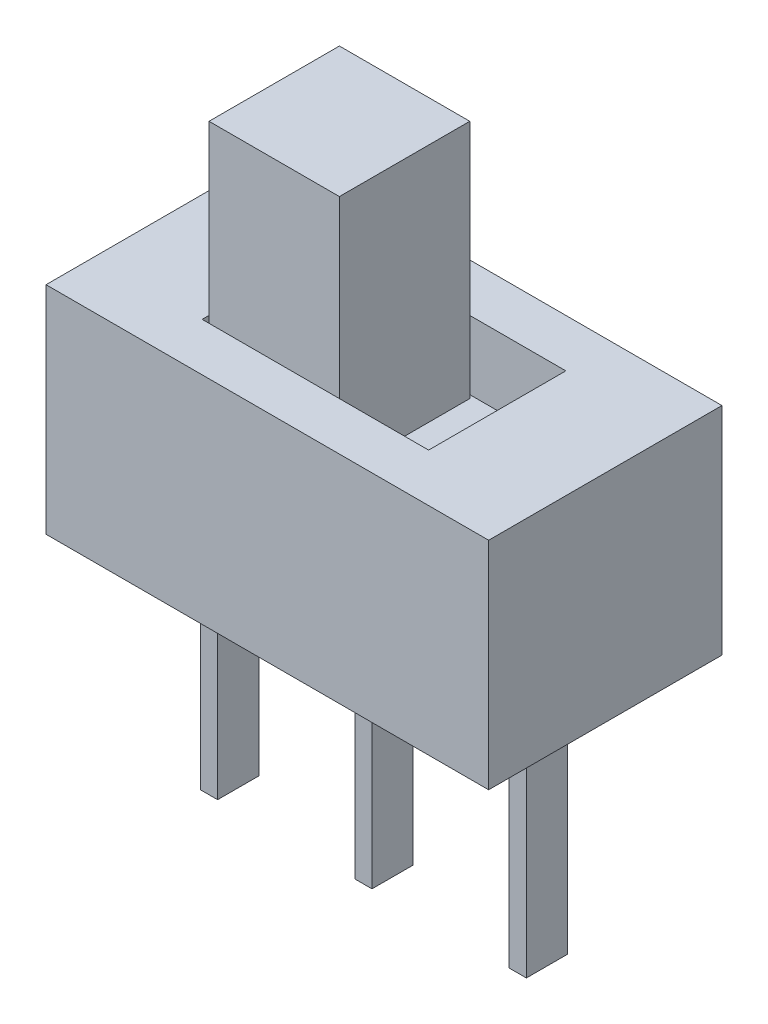
SolidWorks part; units mm, degrees
ref_plane "Front Plane" through (0, 0, 0) normal (0, 0, 1) x (1, 0, 0)
ref_plane "Top Plane" through (0, 0, 0) normal (0, 1, 0) x (1, 0, 0)
ref_plane "Right Plane" through (0, 0, 0) normal (1, 0, 0) x (0, 0, -1)
sketch "Sketch1" plane through (0, 0, 0) normal (0, 1, 0) x (1, 0, 0)
  line L1 (-6.45, 3.4) -> (6.45, 3.4)
  line L2 (-6.45, 3.4) -> (-6.45, -3.4)
  line L3 (-6.45, -3.4) -> (6.45, -3.4)
  line L4 (6.45, 3.4) -> (6.45, -3.4)
  line L5 (0, -3.4) -> (0, 3.4) construction
  line L6 (-6.45, 0) -> (6.45, 0) construction
  point P0 (0, 0)
  dimension "D1" = 12.9
  dimension "D2" = 6.8
extrude "Boss-Extrude1" add sketch "Sketch1" along normal blind 6.3
sketch "Sketch2" plane through (0, 6.3, 0) normal (0, 1, 0) x (1, 0, 0)
  line L0 (0.7, 2) -> (0.7, -2) construction
  line L1 (-3.3, 2) -> (3.3, 2)
  line L2 (-3.3, 2) -> (-3.3, -2)
  line L3 (-3.3, -2) -> (3.3, -2)
  line L4 (3.3, 2) -> (3.3, -2)
  line L5 (0, 2) -> (0, -2) construction
  line L6 (-3.3, 0) -> (0.7, 0) construction
  line L9 (-6.45, 3.4) -> (-6.45, -3.4) construction
  point P12 (0, 0)
  dimension "D1" = 4
  dimension "D2" = 2.6
  dimension "D3" = 3.15
  dimension "D4" = 6.6
extrude "Cut-Extrude1" cut sketch "Sketch2" against normal blind 2
sketch "Sketch3" plane through (0, 4.3, 0) normal (0, 1, 0) x (1, 0, 0)
  line L0 (-3.465, 0) -> (3.465, 0) construction
  line L5 (-3.2, 1.9) -> (0.6, 1.9)
  line L6 (-3.2, 1.9) -> (-3.2, -1.9)
  line L7 (-3.2, -1.9) -> (0.6, -1.9)
  line L8 (0.6, 1.9) -> (0.6, -1.9)
  line L9 (-1.3, -1.9) -> (-1.3, 1.9) construction
  line L10 (-3.2, 0) -> (0.6, 0) construction
  line L11 (3.3, 2) -> (-3.3, 2) construction
  line L12 (-3.3, 2) -> (-3.3, -2) construction
  point P0 (-1.3, 0)
  dimension "D1" = 0.1
  dimension "D2" = 0.1
extrude "Boss-Extrude3" add sketch "Sketch3" along normal offset from surface (7 mm away) 5 up to face at (0, 6.3, 0) offset beyond the face yes
sketch "Sketch4" plane through (0, 0, 0) normal (0, -1, 0) x (1, 0, 0)
  line L1 (-0.25, 0.6) -> (0.25, 0.6)
  line L2 (-0.25, 0.6) -> (-0.25, -0.6)
  line L3 (-0.25, -0.6) -> (0.25, -0.6)
  line L4 (0.25, 0.6) -> (0.25, -0.6)
  line L5 (0, -0.6) -> (0, 0.6) construction
  line L6 (-0.25, 0) -> (0.25, 0) construction
  point P0 (0, 0)
  dimension "D1" = 0.5
  dimension "D2" = 1.2
extrude "Boss-Extrude4" add sketch "Sketch4" along normal blind 7
pattern_linear "LPattern1" count 2 spacing 4.5 along (1, 0, 0) count 2 spacing 4.5 along (-1, 0, 0) of "Boss-Extrude4"
equation "\"D1@Sketch2\"=3.8 + 0.1 * 2"
equation "\"D1@Boss-Extrude3\" = 2 + 5.5"
equation "\"D2@Sketch2\"= 2.5 + 0.1"
